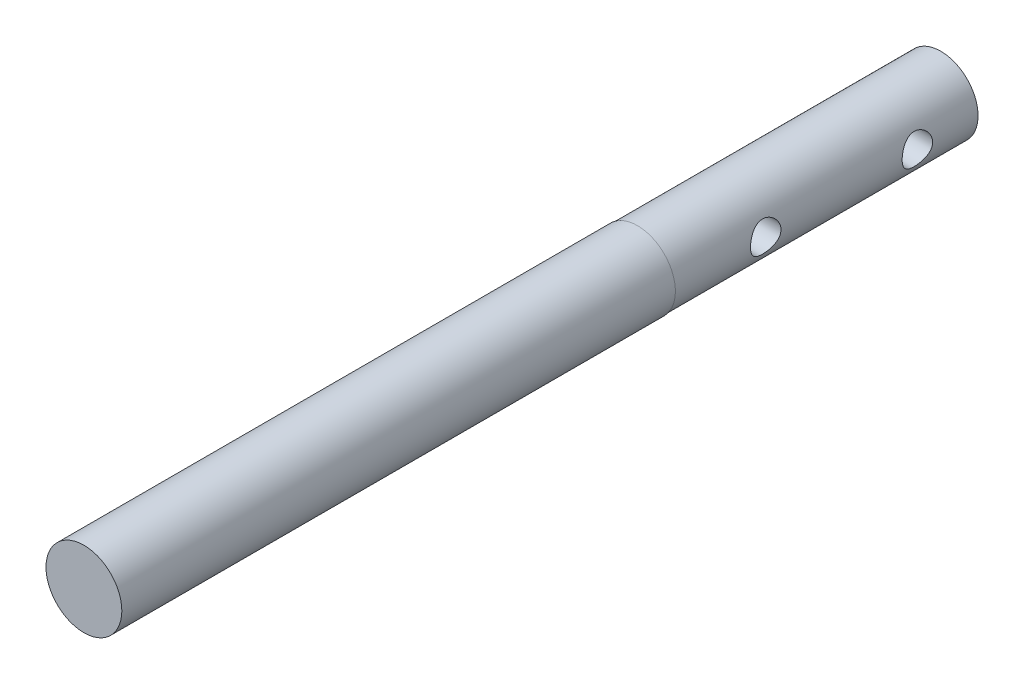
SolidWorks part; units mm, degrees
material "AISI 304"
ref_plane "Front Plane" through (0, 0, 0) normal (0, 0, 1) x (1, 0, 0)
ref_plane "Top Plane" through (0, 0, 0) normal (0, 1, 0) x (1, 0, 0)
ref_plane "Right Plane" through (0, 0, 0) normal (1, 0, 0) x (0, 0, -1)
sketch "Sketch1" plane through (0, 0, 0) normal (0, 0, 1) x (1, 0, 0)
  circle A0 centre (0, 0) radius 25
  dimension "D1" = 50
extrude "Boss-Extrude1" add sketch "Sketch1" along normal mid plane 565
sketch "Sketch2" plane through (0, 0, 0) normal (1, 0, 0) x (0, 0, -1)
  line L0 (-282.5, 0) -> (0, 0) construction
  line L1 (-282.5, 25) -> (-282.5, -25) construction
  circle A0 centre (142.5, 0) radius 10.05
  circle A1 centre (242.5, 0) radius 10.05
  dimension "D1" = 20.1
  dimension "D3" = 100
  dimension "D2" = 425
extrude "Cut-Extrude1" cut sketch "Sketch2" against normal through all both and the other way through all
ref_plane "Plane1" through (-18.5, 0, 0) normal (1, 0, 0) x (0, 0, -1)
sketch "Sketch3" plane through (-18.5, 0, 0) normal (1, 0, 0) x (0, 0, -1)
  line L0 (-282.5, 0) -> (-27.9799, 0) construction
  line L1 (-282.5, 25) -> (-282.5, -25) construction
  line L3 (-262.5, -7) -> (-220.5, -7)
  line L5 (-262.5, 7) -> (-220.5, 7)
  arc A0 (-262.5, 7) -> (-262.5, -7) centre (-262.5, 0) ccw
  arc A1 (-220.5, -7) -> (-220.5, 7) centre (-220.5, 0) ccw
  dimension "D2" = 7
  dimension "D1" = 42
  dimension "D3" = 20
extrude "Cut-Extrude2" cut sketch "Sketch3" against normal blind 10
sketch "Sketch4" plane through (0, 0, -282.5) normal (0, 0, -1) x (-1, 0, 0)
  circle A0 centre (0, 0) radius 24.61
  dimension "D1" = 49.22
extrude "Cut-Extrude3" cut sketch "Sketch4" against normal blind 200 flip side to cut
